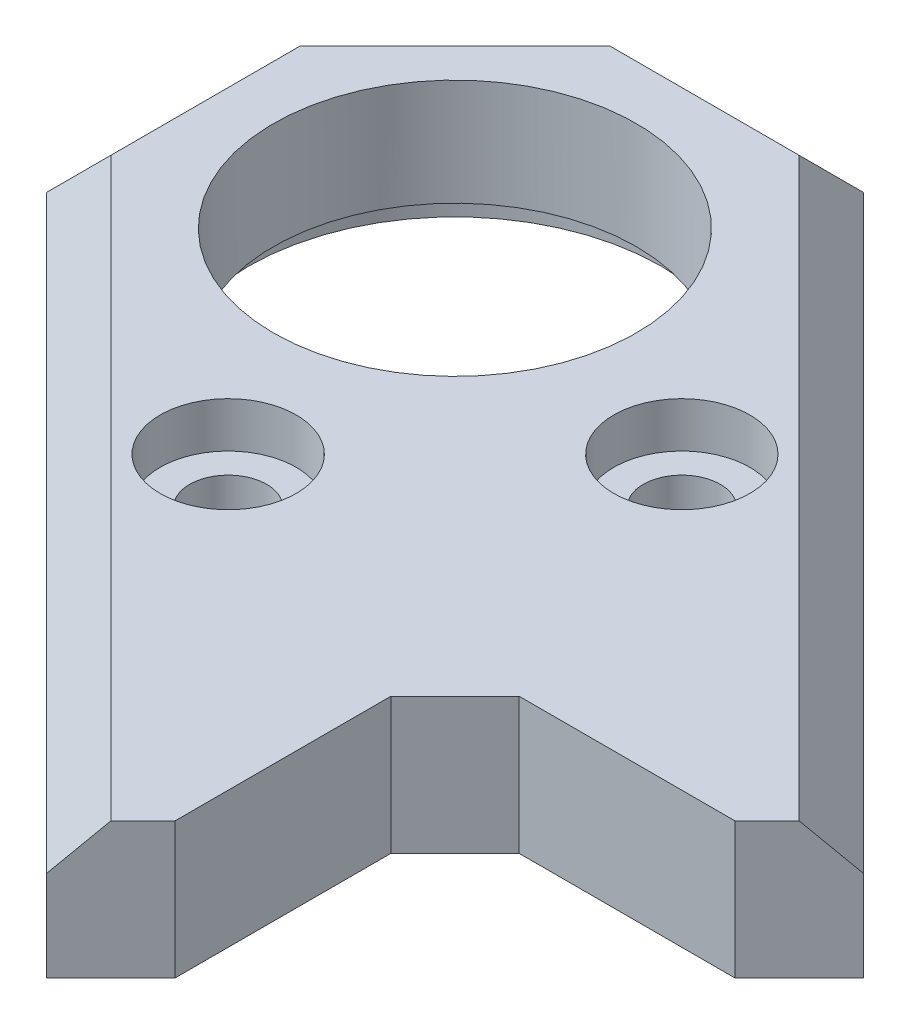
SolidWorks part; units mm, degrees
ref_plane "Front Plane" through (0, 0, 0) normal (0, 0, 1) x (1, 0, 0)
ref_plane "Top Plane" through (0, 0, 0) normal (0, 1, 0) x (1, 0, 0)
ref_plane "Right Plane" through (0, 0, 0) normal (1, 0, 0) x (0, 0, -1)
sketch "Sketch2" plane through (0, 0, 0) normal (0, 1, 0) x (1, 0, 0)
  line L1 (-22, 22) -> (22, 22)
  line L2 (-22, 22) -> (-22, -22)
  line L3 (-22, -22) -> (22, -22)
  line L4 (22, 22) -> (22, -22)
  line L5 (-22, 22) -> (22, -22) construction
  line L6 (-22, -22) -> (22, 22) construction
  point P0 (0, 0)
  dimension "D1" = 44
  dimension "D2" = 44
extrude "Boss-Extrude1" add sketch "Sketch2" along normal blind 6
chamfer "Chamfer1" distance 18 angle 45 1 edges at (22, 3, 22)
sketch "Sketch3" plane through (0, 6, 0) normal (0, 1, 0) x (1, 0, 0)
  line L0 (4, -22) -> (22, -4) construction
  circle A0 centre (-9.6298, 9.625) radius 8
  point P4 (-9.3327, 6.4222)
  point P8 (0, 0)
  point P10 (0, 0)
  dimension "D3" = 16
  dimension "D1" = 32
  dimension "D2" = 13.625
extrude "Cut-Extrude1" cut sketch "Sketch3" against normal through all
sketch "Sketch4" plane through (0, 0, 0) normal (0, -1, 0) x (-1, 0, 0)
  circle A0 centre (9.6298, 9.625) radius 9.1
  dimension "D1" = 18.2
extrude "Cut-Extrude2" cut sketch "Sketch4" against normal blind 1.3
sketch "Sketch5" plane through (0, 6, 0) normal (0, 1, 0) x (1, 0, 0)
  line L0 (-14, 22) -> (-22, 14)
  line L1 (22, 22) -> (-22, 22) construction
  line L2 (-22, 22) -> (-22, -22) construction
  line L3 (-22, 14) -> (-22, 22)
  line L4 (-22, 22) -> (-14, 22)
  dimension "D1" = 8
  dimension "D2" = 8
extrude "Cut-Extrude3" cut sketch "Sketch5" against normal through all
sketch "Sketch7" plane through (0, 6, 0) normal (0, 1, 0) x (1, 0, 0)
  line L0 (-4, 22) -> (22, -4)
  line L1 (22, 22) -> (-14, 22) construction
  line L2 (22, -4) -> (22, 22) construction
  line L3 (22, -4) -> (22, 22)
  line L4 (22, 22) -> (-4, 22)
  line L5 (-22, 4) -> (4, -22)
  line L6 (-22, 14) -> (-22, -22) construction
  line L7 (-22, -22) -> (4, -22) construction
  line L8 (4, -22) -> (-22, -22)
  line L9 (-22, -22) -> (-22, 4)
  line L10 (19.1716, -6.8284) -> (9.6569, -6.8284)
  line L11 (4, -22) -> (22, -4) construction
  line L12 (9.6569, -6.8284) -> (6.8284, -9.6569)
  line L13 (6.8284, -9.6569) -> (6.8284, -19.1716)
  line L14 (6.8284, -19.1716) -> (19.1716, -6.8284)
  circle A0 centre (4, 6) radius 1.7
  circle A1 centre (-6, -4) radius 1.7
  point P25 (4.8073, 4)
  point P26 (4, 5.9106)
  point P27 (0, 0)
  point P28 (0, 0)
  dimension "D8" = 3.4
  dimension "D9" = 18
  dimension "D1" = 26
  dimension "D2" = 26
  dimension "D3" = 26
  dimension "D4" = 26
  dimension "D5" = 4
  dimension "D6" = 4
  dimension "D7" = 4
  dimension "D10" = 18
  dimension "D11" = 10
  dimension "D12" = 10
extrude "Cut-Extrude4" cut sketch "Sketch7" against normal through all
sketch "Sketch8" plane through (0, 6, 0) normal (0, 1, 0) x (1, 0, 0)
  circle A0 centre (4, 6) radius 3
  circle A1 centre (-6, -4) radius 3
  dimension "D1" = 6
extrude "Cut-Extrude5" cut sketch "Sketch8" against normal blind 2
chamfer "Chamfer2" distance 2 angle 45 5 edges at (-9, 6, 9) (9, 6, -9) (-9, 6, -22) (-18, 6, -18) (-22, 6, -9)
